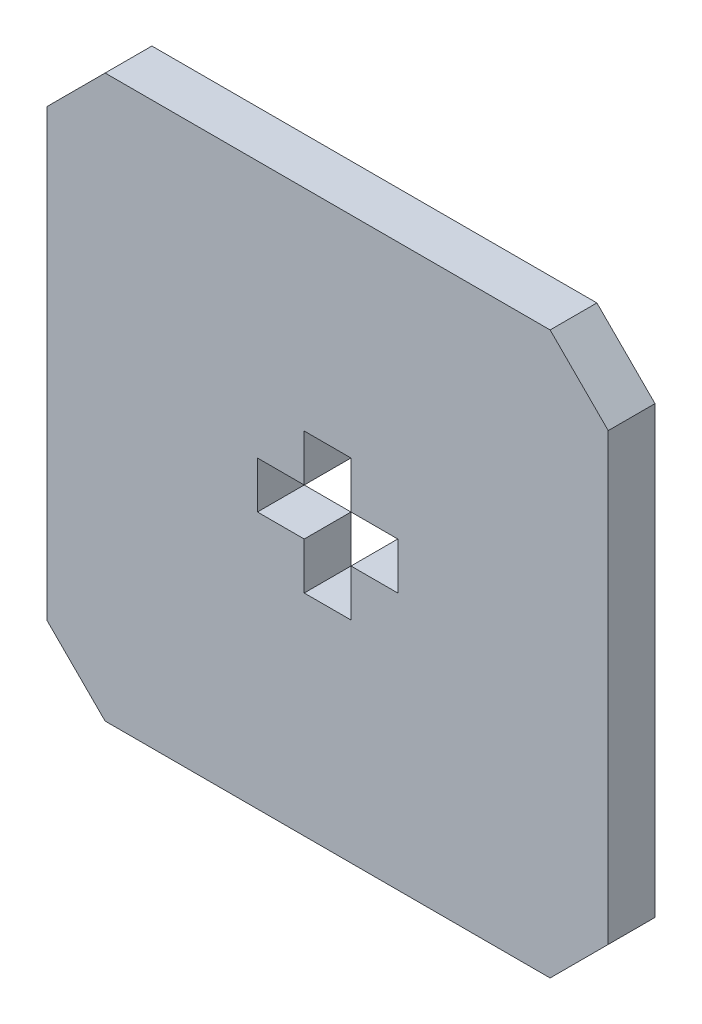
SolidWorks part; units mm, degrees
ref_plane "Front Plane" through (0, 0, 0) normal (0, 0, 1) x (1, 0, 0)
ref_plane "Top Plane" through (0, 0, 0) normal (0, 1, 0) x (1, 0, 0)
ref_plane "Right Plane" through (0, 0, 0) normal (1, 0, 0) x (0, 0, -1)
sketch "Sketch1" plane through (0, 0, 0) normal (0, 0, 1) x (1, 0, 0)
  line L1065 (454.5, 274.5) -> (454.5, 277.5)
  line L1066 (454.5, 277.5) -> (457.5, 277.5)
  line L1067 (457.5, 277.5) -> (457.5, 280.5)
  line L1068 (457.5, 280.5) -> (454.5, 280.5)
  line L1069 (454.5, 280.5) -> (454.5, 283.5)
  line L1070 (454.5, 283.5) -> (451.5, 283.5)
  line L1071 (451.5, 283.5) -> (451.5, 280.5)
  line L1072 (451.5, 280.5) -> (448.5, 280.5)
  line L1073 (448.5, 280.5) -> (448.5, 277.5)
  line L1074 (448.5, 277.5) -> (451.5, 277.5)
  line L1075 (451.5, 277.5) -> (451.5, 274.5)
  line L1076 (451.5, 274.5) -> (454.5, 274.5)
  line L1077 (471, 293.2721) -> (467.2721, 297)
  line L1078 (467.2721, 297) -> (438.7279, 297)
  line L1079 (438.7279, 297) -> (435, 293.2721)
  line L1080 (435, 293.2721) -> (435, 264.7279)
  line L1081 (435, 264.7279) -> (438.7279, 261)
  line L1082 (438.7279, 261) -> (467.2721, 261)
  line L1083 (467.2721, 261) -> (471, 264.7279)
  line L1084 (471, 264.7279) -> (471, 293.2721)
extrude "Boss-Extrude1" add sketch "Sketch1" along normal blind 3
